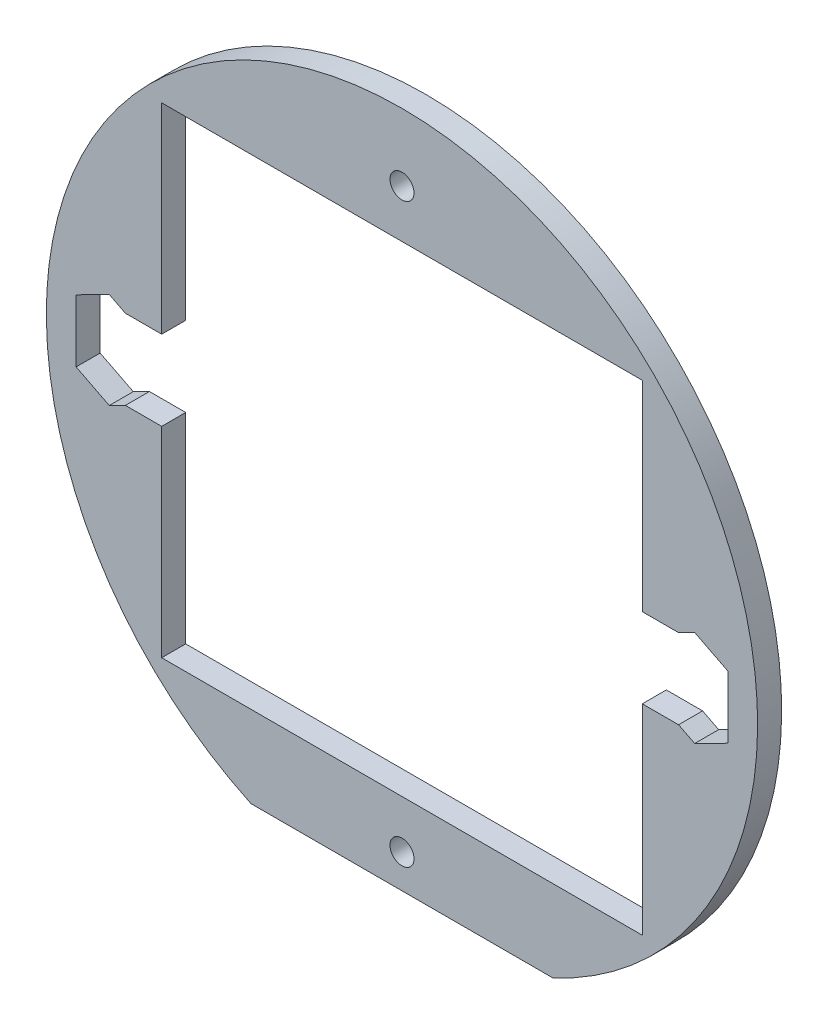
SolidWorks part; units mm, degrees
ref_plane "Front Plane" through (0, 0, 0) normal (0, 0, 1) x (1, 0, 0)
ref_plane "Top Plane" through (0, 0, 0) normal (0, 1, 0) x (1, 0, 0)
ref_plane "Right Plane" through (0, 0, 0) normal (1, 0, 0) x (0, 0, -1)
sketch "Sketch1" plane through (0, 0, 0) normal (0, 0, 1) x (1, 0, 0)
  line L0 (0, -60) -> (0, -67)
  line L1 (-50, 50) -> (50, 50)
  line L2 (-50, 50) -> (-50, -50)
  line L3 (-50, -50) -> (50, -50)
  line L4 (50, 50) -> (50, -50)
  line L5 (-50, 50) -> (50, -50) construction
  line L6 (-50, -50) -> (50, 50) construction
  line L7 (0, -67) -> (-31.4166, -67)
  line L8 (-31.4166, -67) -> (31.4166, -67)
  arc A0 (31.4166, -67) -> (-31.4166, -67) centre (0, 0) ccw
  circle A1 centre (0, 60) radius 2.5
  circle A3 centre (0, -60) radius 2.5
  point P1 (0, 0)
  point P11 (0, 0)
  point P15 (-31.4166, -67)
  point P18 (31.4166, -67)
  dimension "D1" = 148
  dimension "D4" = 60
  dimension "D10" = 60
  dimension "D2" = 100
  dimension "D3" = 100
  dimension "D5" = 50
  dimension "D11" = 50
  dimension "D12" = 7
  dimension "D13" = 7
extrude "circle" add sketch "Sketch1" along normal blind 5 contours L8 A0
sketch "Sketch2" plane through (0, 0, 5) normal (0, 0, 1) x (1, 0, 0)
  line L1 (50, 50) -> (-50, 50)
  line L2 (50, 50) -> (50, -50)
  line L3 (50, -50) -> (-50, -50)
  line L4 (-50, 50) -> (-50, -50)
  line L5 (50, 50) -> (-50, -50) construction
  line L6 (50, -50) -> (-50, 50) construction
  point P0 (0, 0)
  dimension "D1" = 100
  dimension "D2" = 100
extrude "square" cut sketch "Sketch2" against normal blind 5
sketch "Sketch3" plane through (0, 0, 5) normal (0, 0, 1) x (1, 0, 0)
  line L0 (50, -50) -> (50, 50) construction
  circle A0 centre (0, 60) radius 2.5
  circle A1 centre (0, -60) radius 2.5
  arc A3 (31.4166, -67) -> (-31.4166, -67) centre (0, 0) ccw construction
  point P7 (0, 0)
  point P9 (0, 0)
  point P13 (0, 0)
  dimension "D1" = 50
  dimension "D2" = 50
  dimension "D3" = 60
  dimension "D4" = 60
extrude "holes" cut sketch "Sketch3" against normal blind 5
sketch "Sketch4" plane through (0, 0, 5) normal (0, 0, 1) x (1, 0, 0)
  line L5 (-50, 0) -> (-50, -8.3)
  line L6 (-50, 50) -> (-50, -50) construction
  line L7 (-50, -8.3) -> (-57.55, -8.3)
  line L8 (-57.55, -8.3) -> (-60.9037, -10)
  line L9 (-60.9037, -10) -> (-67.8072, -6.5)
  line L10 (-67.8072, -6.5) -> (-67.8072, 6.5)
  line L11 (-67.8072, 6.5) -> (-60.9037, 10)
  line L12 (-60.9037, 10) -> (-57.55, 8.3)
  line L13 (-57.55, 8.3) -> (-50, 8.3)
  line L14 (-50, 8.3) -> (-50, 0)
  line L16 (57.55, 8.3) -> (50, 8.3)
  line L17 (60.9037, 10) -> (57.55, 8.3)
  line L18 (67.8072, 6.5) -> (60.9037, 10)
  line L19 (67.8072, -6.5) -> (67.8072, 6.5)
  line L20 (60.9037, -10) -> (67.8072, -6.5)
  line L21 (57.55, -8.3) -> (60.9037, -10)
  line L22 (50, -8.3) -> (57.55, -8.3)
  line L23 (50, 0) -> (50, -8.3)
  line L24 (50, 8.3) -> (50, 0)
  dimension "D1" = 13
  dimension "D2" = 7.74
  dimension "D3" = 7.74
  dimension "D4" = 16.6
  dimension "D5" = 8.3
  dimension "D6" = 8.3
  dimension "D7" = 7.55
  dimension "D8" = 7.55
  dimension "D9" = 3.76
  dimension "D10" = 3.76
  dimension "D11" = 3.5
  dimension "D12" = 1.7
  dimension "D13" = 1.7
  dimension "D14" = 17.8072
  dimension "D15" = 3.5
extrude "Cut-Extrude3" cut sketch "Sketch4" against normal blind 5
